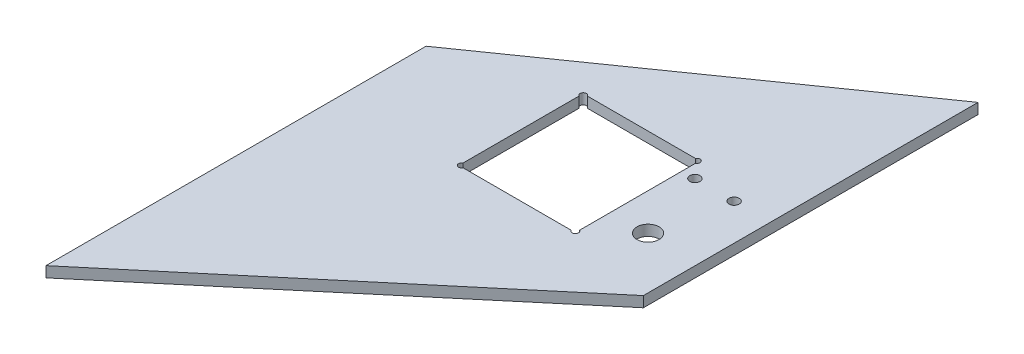
SolidWorks part; units mm, degrees
ref_plane "Front Plane" through (0, 0, 0) normal (0, 0, 1) x (1, 0, 0)
ref_plane "Top Plane" through (0, 0, 0) normal (0, 1, 0) x (1, 0, 0)
ref_plane "Right Plane" through (0, 0, 0) normal (1, 0, 0) x (0, 0, -1)
sketch "Sketch1" plane through (0, 0, 0) normal (0, 1, 0) x (1, 0, 0)
  line L0 (0, -9.9305) -> (0, 126.604)
  line L1 (0, -9.9305) -> (116.6193, 88.0595)
  line L2 (0, 126.604) -> (116.6193, 208.2617)
  line L3 (116.6193, -930.5509) -> (116.6193, 49069.4491) construction
  line L4 (116.6193, 208.2617) -> (116.6193, 88.0595)
  line B0 (42.9822, 138.7989) -> (84.8253, 138.7989)
  line B1 (42.9822, 138.7989) -> (42.9822, 96.7619)
  line B2 (42.9822, 96.7619) -> (84.8253, 96.7619)
  line B3 (84.8253, 138.7989) -> (84.8253, 96.7619)
  circle B4 centre (98.0424, 108.2999) radius 3.9687
  circle B5 centre (89.4586, 133.7169) radius 1.8288
  circle B6 centre (103.5453, 133.7169) radius 1.8288
sketch_block_instance "Block2-1"
sketch_block "Block2" parameters "D1"=42.037, "D2"=41.843
extrude "Boss-Extrude1" add sketch "Sketch1" along normal blind 2.54 and the other way blind 1.27
sketch "Sketch2" plane through (0, 2.54, 0) normal (0, 1, 0) x (1, 0, 0)
  line L1 (42.9822, 96.7619) -> (84.8253, 96.7619)
  line L2 (42.9822, 96.7619) -> (42.9822, 95.4157)
  line L3 (42.9822, 95.4157) -> (84.8253, 95.4157)
  line L4 (84.8253, 96.7619) -> (84.8253, 95.4157)
  line L5 (42.9822, 138.7989) -> (84.8253, 138.7989)
  line L6 (42.9822, 138.7989) -> (42.9822, 140.0689)
  line L7 (42.9822, 140.0689) -> (84.8253, 140.0689)
  line L8 (84.8253, 138.7989) -> (84.8253, 140.0689)
extrude "Cut-Extrude1" cut sketch "Sketch2" against normal through all
hole_wizard "#43 (0.089) Diameter Hole1" positions "Sketch4" profile "Sketch3" hole size "#43" standard "ANSI Inch" end condition through all
sketch "Sketch4" plane through (0, 2.54, 0) normal (0, 1, 0) x (1, 0, 0)
  line L18 (84.8253, 95.4157) -> (84.8253, 140.0689) construction
  line L22 (42.9822, 140.0689) -> (42.9822, 95.4157) construction
  line L25 (84.8253, 140.0689) -> (42.9822, 140.0689) construction
  line L26 (42.9822, 95.4157) -> (84.8253, 95.4157) construction
  point P4 (84.3173, 95.9237)
  point P6 (84.3173, 139.5609)
  point P41 (43.4902, 95.9237)
  point P76 (43.4902, 139.5609)
  dimension "D1" = 0.508
  dimension "D2" = 0.508
  dimension "D3" = 0.508
  dimension "D4" = 0.508
sketch "Sketch3" plane through (84.3173, 2.54, -95.9237) normal (1, 0, 0) x (0, 0, 1)
  line L0 (0, 0) -> (0, 3.81)
  line L1 (0, 3.81) -> (1.1303, 3.81)
  line L2 (1.1303, 3.81) -> (1.1303, 0)
  line L5 (1.1303, 0) -> (0, 0)
  line L11 (0, -6.35) -> (0, 107.95) construction
  dimension "Thru Hole Dia." = 2.2606
  dimension "Thru Hole Depth" = 3.81
